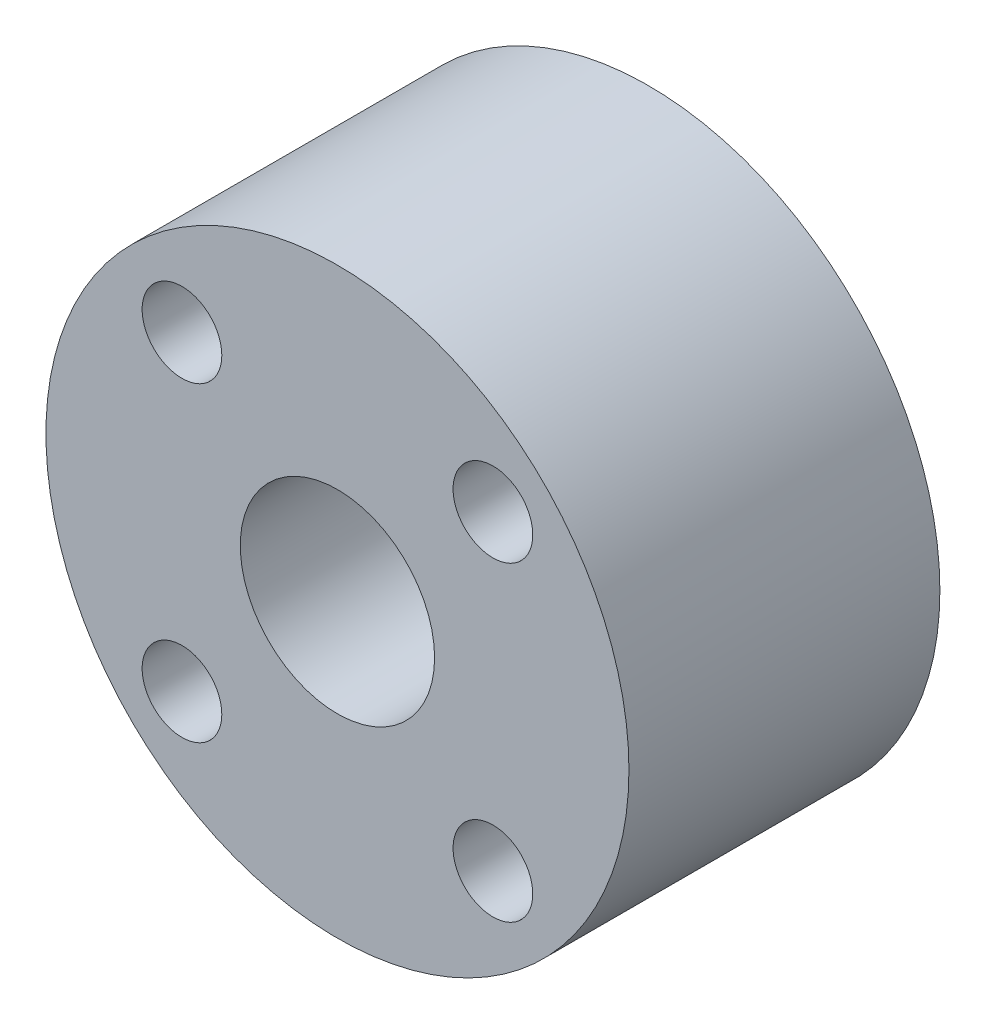
SolidWorks part; units mm, degrees
ref_plane "Front Plane" through (0, 0, 0) normal (0, 0, 1) x (1, 0, 0)
ref_plane "Top Plane" through (0, 0, 0) normal (0, 1, 0) x (1, 0, 0)
ref_plane "Right Plane" through (0, 0, 0) normal (1, 0, 0) x (0, 0, -1)
sketch "Sketch1" plane through (0, 0, 0) normal (0, 0, 1) x (1, 0, 0)
  line L1 (8, -8) -> (-8, -8) construction
  line L2 (8, -8) -> (8, 8) construction
  line L3 (8, 8) -> (-8, 8) construction
  line L4 (-8, -8) -> (-8, 8) construction
  line L5 (8, -8) -> (-8, 8) construction
  line L6 (8, 8) -> (-8, -8) construction
  circle A0 centre (0, 0) radius 15
  circle A1 centre (-8, 8) radius 2.05
  circle A2 centre (8, 8) radius 2.05
  circle A3 centre (8, -8) radius 2.05
  circle A4 centre (-8, -8) radius 2.05
  circle A5 centre (0, 0) radius 5
  dimension "D1" = 30
  dimension "D4" = 10
  dimension "D5" = 4.1
  dimension "D6" = 4.1
  dimension "D7" = 4.1
  dimension "D8" = 4.1
  dimension "D2" = 16
  dimension "D3" = 16
extrude "Boss-Extrude1" add sketch "Sketch1" along normal blind 16
